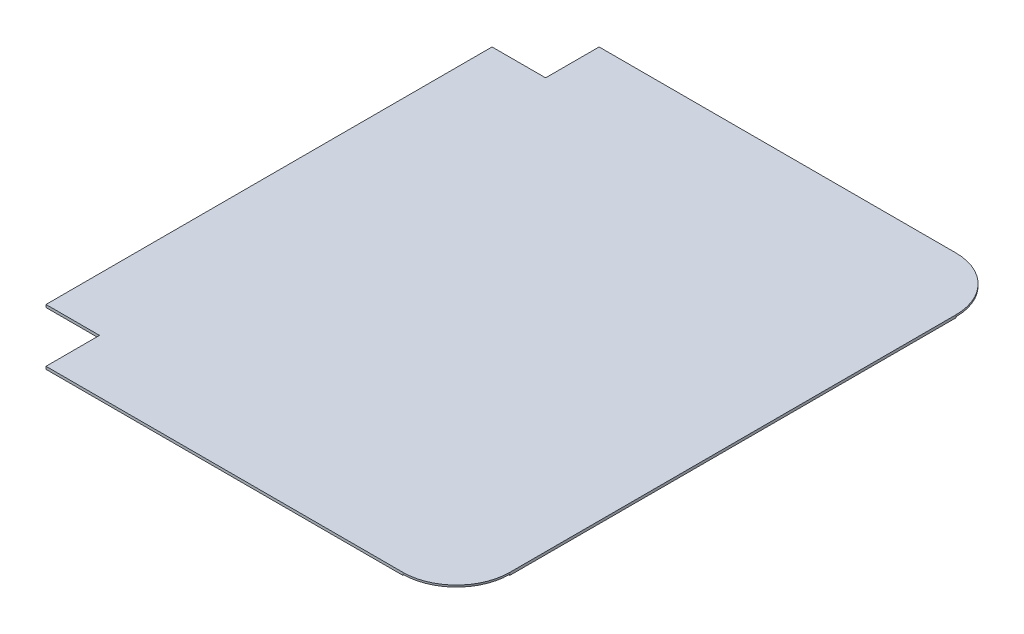
SolidWorks part; units mm, degrees
material "5086-H32，棒材(SS)"
ref_plane "前视基准面" through (0, 0, 0) normal (0, 0, 1) x (1, 0, 0)
ref_plane "上视基准面" through (0, 0, 0) normal (0, 1, 0) x (1, 0, 0)
ref_plane "右视基准面" through (0, 0, 0) normal (1, 0, 0) x (0, 0, -1)
other "Configuration Table"
sketch "草图1" plane through (0, 0, 0) normal (0, 1, 0) x (1, 0, 0)
  line L0 (-240.9174, -196.789) -> (-240.9174, -256.789)
  line L1 (-300.9174, 303.211) -> (-240.9174, 303.211)
  line L2 (-300.9174, 303.211) -> (-300.9174, -196.789)
  line L3 (-300.9174, -196.789) -> (-240.9174, -196.789)
  line L4 (219.0826, 303.211) -> (219.0826, -196.789)
  line L5 (-240.9174, 363.211) -> (159.0826, 363.211)
  line L6 (-240.9174, 363.211) -> (-240.9174, 303.211)
  line L7 (-240.9174, -256.789) -> (159.0826, -256.789)
  line L8 (159.0826, 363.211) -> (159.0826, 303.211)
  line L9 (159.0826, -196.789) -> (159.0826, -256.789)
  line L10 (159.0826, 303.211) -> (219.0826, 303.211)
  line L11 (219.0826, -196.789) -> (159.0826, -196.789)
  dimension "D1" = 500
  dimension "D2" = 400
  dimension "D3" = 60
extrude "凸台-拉伸1" add sketch "草图1" along normal blind 3
sketch "草图2" plane through (0, 3, 0) normal (0, 1, 0) x (1, 0, 0)
  line L2 (-40.9174, 363.211) -> (-40.9174, -256.789) construction
  line L3 (159.0826, 363.211) -> (-240.9174, 363.211) construction
  line L4 (-240.9174, -256.789) -> (159.0826, -256.789) construction
  line L5 (-300.9174, 53.211) -> (219.0826, 53.211) construction
  line L6 (-300.9174, 303.211) -> (-300.9174, -196.789) construction
  line L7 (219.0826, -196.789) -> (219.0826, 303.211) construction
  line L8 (159.0826, 303.211) -> (219.0826, 303.211)
  line L9 (159.0826, 363.211) -> (159.0826, 303.211)
  line L10 (159.0826, -256.789) -> (159.0826, -196.789)
  line L11 (159.0826, -196.789) -> (219.0826, -196.789)
  arc A1 (159.0826, 363.211) -> (219.0826, 303.211) centre (159.0826, 303.211) cw
  arc A2 (159.0826, -256.789) -> (219.0826, -196.789) centre (159.0826, -196.789) ccw
extrude "凸台-拉伸2" add sketch "草图2" against normal blind 2
